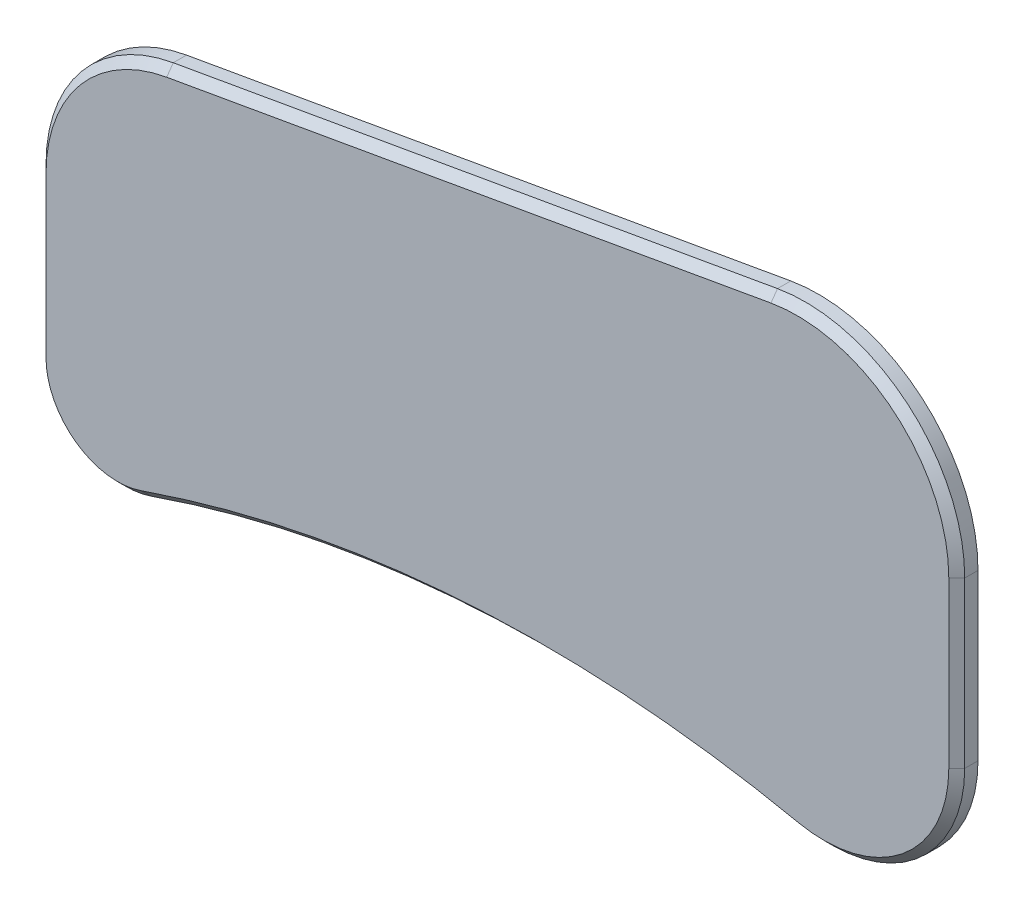
SolidWorks part; units mm, degrees
ref_plane "Front Plane" through (0, 0, 0) normal (0, 0, 1) x (1, 0, 0)
ref_plane "Top Plane" through (0, 0, 0) normal (0, 1, 0) x (1, 0, 0)
ref_plane "Right Plane" through (0, 0, 0) normal (1, 0, 0) x (0, 0, -1)
sketch "Sketch1" plane through (0, 0, 0) normal (0, 0, 1) x (1, 0, 0)
  line L3 (54.7487, 40.101) -> (-59.0358, 20.0378)
  line L4 (-83, -8.5217) -> (-83, -38.5217)
  line L5 (90, -20.5217) -> (90, 10.5217)
  line L6 (54.7487, 40.101) -> (-59.0358, 20.0378)
  line L7 (-83, -8.5217) -> (-83, -38.5217)
  line L8 (90, -20.5217) -> (90, 10.5217)
  arc A5 (-59.0358, 20.0378) -> (-83, -8.5217) centre (-54, -8.5217) ccw
  arc A6 (-83, -38.5217) -> (-63.0867, -52.6942) centre (-68, -38.5217) ccw
  arc A7 (59.8284, -44.9809) -> (-63.0867, -52.6942) centre (12.2498, -270.0059) ccw
  arc A8 (59.8284, -44.9809) -> (90, -20.5217) centre (65, -20.5217) ccw
  arc A9 (90, 10.5217) -> (54.7487, 40.101) centre (59.9643, 10.5217) ccw
  arc A10 (-59.0358, 20.0378) -> (-83, -8.5217) centre (-54, -8.5217) ccw
  arc A11 (-83, -38.5217) -> (-63.0867, -52.6942) centre (-68, -38.5217) ccw
  arc A12 (59.8284, -44.9809) -> (-63.0867, -52.6942) centre (12.2498, -270.0059) ccw
  arc A13 (59.8284, -44.9809) -> (90, -20.5217) centre (65, -20.5217) ccw
  arc A14 (90, 10.5217) -> (54.7487, 40.101) centre (59.9643, 10.5217) ccw
  dimension "D1" = 0
extrude "Boss-Extrude1" add sketch "Sketch1" along normal blind 4
chamfer "Chamfer1" distance 1.5 angle 45 8 edges at (-2.155, -40.4575, 4) (80.7434, -39.9419, 4) (-76.6977, -50.7425, 4) (90, -5, 4) (-83, -23.5217, 4) (79.2709, 33.5303, 4) (-76.2153, 10.1192, 4) (-2.1436, 30.0694, 4)
